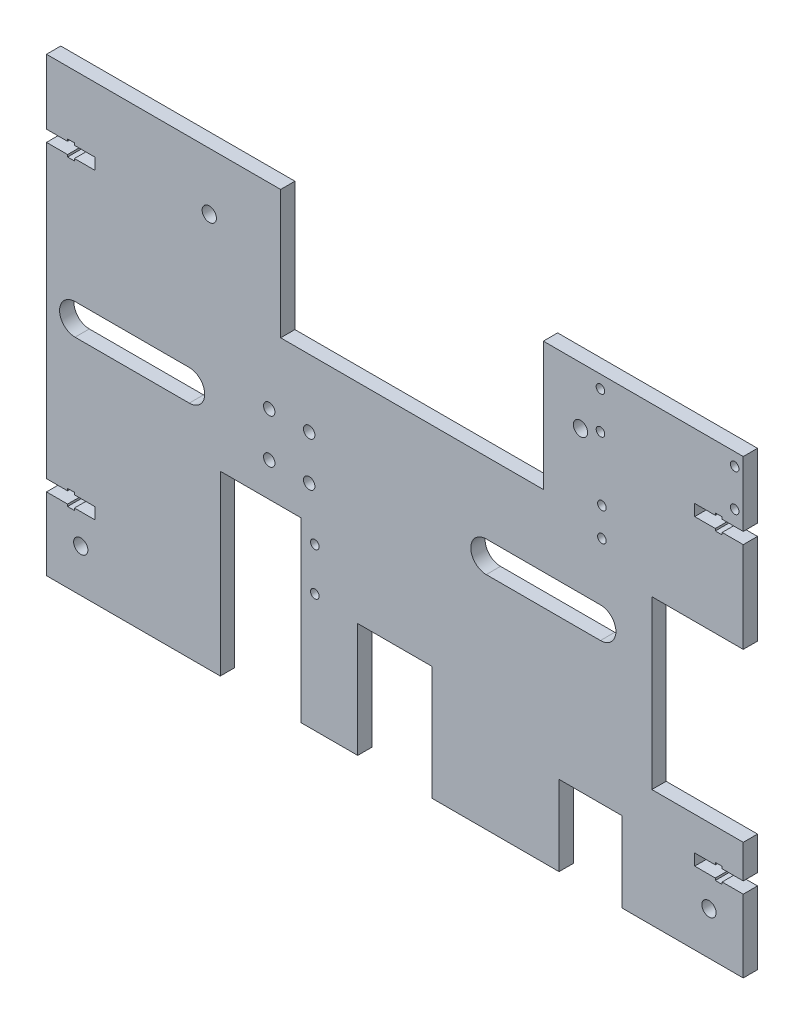
SolidWorks part; units mm, degrees
ref_plane "Front Plane" through (0, 0, 0) normal (0, 0, 1) x (1, 0, 0)
ref_plane "Top Plane" through (0, 0, 0) normal (0, 1, 0) x (1, 0, 0)
ref_plane "Right Plane" through (0, 0, 0) normal (1, 0, 0) x (0, 0, -1)
sketch "Sketch1" plane through (0, 0, 0) normal (0, 0, 1) x (1, 0, 0)
  line L8 (-125, 33.8375) -> (119, 33.8375)
  line L10 (-125, 33.8375) -> (-125, -124.317)
  line L11 (-125, -124.317) -> (119, -124.317)
  line L14 (119, -124.317) -> (119, 33.8375)
  dimension "D1" = 244
  dimension "D2" = 158.1546
extrude "Boss-Extrude2" add sketch "Sketch1" along normal blind 5
sketch "Sketch2" plane through (0, 0, 0) normal (0, 0, -1) x (-1, 0, 0)
  line L0 (125, 33.8375) -> (125, -124.317) construction
  line L1 (64.1433, -124.317) -> (35.8567, -124.317)
  line L6 (125, -124.317) -> (-119, -124.317) construction
  line L13 (35.8567, -62.1857) -> (35.8567, -124.317)
  line L14 (64.1433, -62.1857) -> (64.1433, -124.317)
  line L15 (35.8567, -62.1857) -> (64.1433, -62.1857)
  dimension "D1" = 28.2866
  dimension "D2" = 62.1313
  dimension "D3" = 60.8567
extrude "Cut-Extrude1" cut sketch "Sketch2" against normal blind 10
sketch "Sketch7" plane through (0, 0, 0) normal (0, 0, -1) x (-1, 0, 0)
  line L0 (-119, -83.1625) -> (-119, 1.3375)
  line L1 (-119, 1.3375) -> (-87, 1.3375)
  line L3 (-119, -83.1625) -> (-87, -83.1625)
  line L4 (-87, 1.3375) -> (-87, -83.1625)
  line L5 (-119, 33.8375) -> (125, 33.8375) construction
  line L9 (-119, -124.317) -> (-119, 33.8375) construction
  dimension "D1" = 32.5
  dimension "D2" = 84.5
  dimension "D3" = 32
extrude "Cut-Extrude5" cut sketch "Sketch7" against normal blind 10
sketch "Sketch9" plane through (0, 0, 0) normal (0, 0, -1) x (-1, 0, 0)
  line L0 (64.1433, -62.1857) -> (35.8567, -62.1857) construction
  line L1 (35.8567, -62.1857) -> (35.8567, -124.317) construction
  circle A0 centre (31.0266, -67.8357) radius 1.5
  circle A2 centre (31.0266, -82.8357) radius 1.5
  dimension "D1" = 3
  dimension "D2" = 3
  dimension "D3" = 5.65
  dimension "D4" = 15
  dimension "D5" = 4.8301
extrude "Cut-Extrude7" cut sketch "Sketch9" against normal blind 10
sketch "Sketch10" plane through (0, 0, 0) normal (0, 0, -1) x (-1, 0, 0)
  line L1 (125, 33.8375) -> (125, -124.317) construction
  line L3 (-10, -124.317) -> (16, -124.317)
  line L5 (35.8567, -124.317) -> (-119, -124.317) construction
  line L7 (-10, -84.317) -> (-10, -124.317)
  line L8 (16, -84.317) -> (16, -124.317)
  line L10 (16, -84.317) -> (-10, -84.317)
  dimension "D3" = 40
  dimension "D4" = 26
  dimension "D5" = 109
extrude "Cut-Extrude8" cut sketch "Sketch10" against normal blind 10
sketch "Sketch12" plane through (0, 0, 0) normal (0, 0, -1) x (-1, 0, 0)
  line L0 (-49, 33.8375) -> (-49, -11.1625)
  line L1 (-119, 33.8375) -> (125, 33.8375) construction
  line L2 (-49, -11.1625) -> (43, -11.1625)
  line L3 (43, 33.8375) -> (43, -11.1625)
  line L4 (-49, 33.8375) -> (43, 33.8375)
  line L5 (125, 33.8375) -> (125, -124.317) construction
  line L6 (-119, 1.3375) -> (-119, 33.8375) construction
  dimension "D1" = 82
  dimension "D2" = 70
  dimension "D3" = 45
extrude "Cut-Extrude10" cut sketch "Sketch12" against normal blind 10
sketch "Sketch13" plane through (0, 0, 0) normal (0, 0, -1) x (-1, 0, 0)
  line L0 (-119, 33.8375) -> (-49, 33.8375) construction
  line L1 (-49, 33.8375) -> (-49, -11.1625) construction
  line L2 (-119, -124.317) -> (-119, -83.1625) construction
  line L3 (-10, -124.317) -> (-119, -124.317) construction
  line L4 (125, 33.8375) -> (125, -124.317) construction
  circle A1 centre (-107, -109.317) radius 2.5
  circle A2 centre (113, -109.317) radius 2.5
  circle A3 centre (-62, 13.8375) radius 2.5
  circle A4 centre (68, 13.8375) radius 2.5
  dimension "D2" = 5
  dimension "D3" = 5
  dimension "D4" = 5
  dimension "D5" = 5
  dimension "D1" = 20
  dimension "D6" = 13
  dimension "D7" = 130
  dimension "D8" = 12
  dimension "D9" = 15
  dimension "D10" = 12
extrude "Cut-Extrude11" cut sketch "Sketch13" against normal blind 10
sketch "Sketch14" plane through (0, 0, 0) normal (0, 0, -1) x (-1, 0, 0)
  line L0 (-109.2131, 11.1143) -> (-102, 11.1143)
  line L1 (-111.6131, 7.1143) -> (-119, 7.1143)
  line L3 (-119, -98.8857) -> (-111.6131, -98.8857)
  line L5 (-111.6131, -98.8857) -> (-111.6131, -99.6357)
  line L7 (-111.6131, -99.6357) -> (-109.2131, -99.6357)
  line L8 (-111.6131, 11.1143) -> (-111.6131, 11.8643)
  line L9 (-119, -43.8857) -> (-47.0288, -43.8857) construction
  line L10 (-119, 33.8375) -> (-49, 33.8375) construction
  line L11 (-109.2131, -99.6357) -> (-109.2131, -98.8857)
  line L12 (-109.2131, -98.8857) -> (-102, -98.8857)
  line L13 (3, 33.8375) -> (125, 33.8375) construction
  line L14 (3, 33.8375) -> (3, -136.7517) construction
  line L15 (-119, 11.1143) -> (-111.6131, 11.1143)
  line L16 (-119, 1.3375) -> (-119, 33.8375) construction
  line L17 (-102, 11.1143) -> (-102, 7.1143)
  line L18 (-102, 7.1143) -> (-109.2131, 7.1143)
  line L19 (-111.6131, 11.8643) -> (-109.2131, 11.8643)
  line L20 (-109.2131, 11.8643) -> (-109.2131, 11.1143)
  line L21 (-109.2131, 7.1143) -> (-109.2131, 6.3643)
  line L22 (-109.2131, 6.3643) -> (-111.6131, 6.3643)
  line L23 (-111.6131, 6.3643) -> (-111.6131, 7.1143)
  line L24 (-87, 1.3375) -> (-119, 1.3375) construction
  line L25 (-119, 11.1143) -> (-119, 7.1143)
  line L26 (-102, -98.8857) -> (-102, -94.8857)
  line L27 (-102, -94.8857) -> (-109.2131, -94.8857)
  line L28 (-109.2131, -94.8857) -> (-109.2131, -94.1357)
  line L29 (-109.2131, -94.1357) -> (-111.6131, -94.1357)
  line L30 (-111.6131, -94.1357) -> (-111.6131, -94.8857)
  line L31 (-111.6131, -94.8857) -> (-119, -94.8857)
  line L32 (-119, -98.8857) -> (-119, -94.8857)
  line L33 (125, -98.8857) -> (125, -94.8857)
  line L34 (117.6131, -94.8857) -> (125, -94.8857)
  line L35 (117.6131, -94.1357) -> (117.6131, -94.8857)
  line L36 (115.2131, -94.1357) -> (117.6131, -94.1357)
  line L37 (115.2131, -94.8857) -> (115.2131, -94.1357)
  line L38 (108, -94.8857) -> (115.2131, -94.8857)
  line L39 (108, -98.8857) -> (108, -94.8857)
  line L40 (115.2131, -98.8857) -> (108, -98.8857)
  line L41 (115.2131, -99.6357) -> (115.2131, -98.8857)
  line L42 (117.6131, -99.6357) -> (115.2131, -99.6357)
  line L43 (117.6131, -98.8857) -> (117.6131, -99.6357)
  line L44 (125, -98.8857) -> (117.6131, -98.8857)
  line L45 (125, 11.1143) -> (117.6131, 11.1143)
  line L46 (117.6131, 11.1143) -> (117.6131, 11.8643)
  line L47 (117.6131, 11.8643) -> (115.2131, 11.8643)
  line L48 (115.2131, 11.8643) -> (115.2131, 11.1143)
  line L49 (115.2131, 11.1143) -> (108, 11.1143)
  line L50 (108, 11.1143) -> (108, 7.1143)
  line L51 (108, 7.1143) -> (115.2131, 7.1143)
  line L52 (115.2131, 7.1143) -> (115.2131, 6.3643)
  line L53 (115.2131, 6.3643) -> (117.6131, 6.3643)
  line L54 (117.6131, 6.3643) -> (117.6131, 7.1143)
  line L55 (117.6131, 7.1143) -> (125, 7.1143)
  line L56 (125, 11.1143) -> (125, 7.1143)
  line M9 (-119, 33.8375) -> (-119, 1.3375)
  line M13 (-119, -83.1625) -> (-119, -124.317)
  line M23 (125, -124.317) -> (125, 33.8375)
  dimension "D1" = 22.7232
  dimension "D2" = 5.7768
  dimension "D3" = 17
  dimension "D4" = 7.3869
  dimension "D5" = 2.4
  dimension "D6" = 0.75
  dimension "D7" = 0.75
  dimension "D8" = 2.4
  dimension "D9" = 77.7232
extrude "Cut-Extrude12" cut sketch "Sketch14" against normal blind 10 contours L30 L31 L3 L5 L7 L11 L12 L26 L27 L28 L29 M13 | L23 L22 L21 L18 L17 L0 L20 L19 L8 L15 L1 M9 | L54 L55 L45 L46 L47 L48 L49 L50 L51 L52 L53 M23 | L44 L34 L35 L36 L37 L38 L39 L40 L41 L42 L43 M23
sketch "Sketch15" plane through (0, 0, 0) normal (0, 0, -1) x (-1, 0, 0)
  line L0 (-119, 1.3375) -> (-119, -24.6625)
  line L1 (-119, -24.6625) -> (-87, -24.6625)
  line L2 (-87, -83.1625) -> (-87, 1.3375) construction
  line L3 (-87, -24.6625) -> (-87, 1.3375)
  line L4 (-87, 1.3375) -> (-119, 1.3375) construction
  line L5 (-119, 1.3375) -> (-87, 1.3375)
  dimension "D1" = 26
extrude "Boss-Extrude3" add sketch "Sketch15" against normal blind 5
sketch "Sketch16" plane through (0, 0, 0) normal (0, 0, -1) x (-1, 0, 0)
  line L0 (-119, -24.6625) -> (-119, 7.1143) construction
  line L1 (-119, 33.8375) -> (-49, 33.8375) construction
  circle A0 centre (-69.5, -5.7627) radius 1.5
  circle A1 centre (-69.5, -15.7627) radius 1.5
  dimension "D1" = 3
  dimension "D2" = 3
  dimension "D3" = 49.5
  dimension "D4" = 39.6002
  dimension "D5" = 10
extrude "Cut-Extrude13" cut sketch "Sketch16" against normal blind 10
sketch "Sketch17" plane through (0, 0, 0) normal (0, 0, -1) x (-1, 0, 0)
  line L0 (-119, 11.1143) -> (-119, 33.8375) construction
  line L1 (-119, 33.8375) -> (-49, 33.8375) construction
  circle A1 centre (-69, 16.3375) radius 1.5
  circle A3 centre (-69, 29.3375) radius 1.5
  circle A5 centre (-116, 16.3375) radius 1.5
  circle A7 centre (-116, 29.3375) radius 1.5
  dimension "D1" = 3
  dimension "D2" = 3
  dimension "D3" = 3
  dimension "D4" = 3
  dimension "D5" = 3
  dimension "D6" = 4.5
  dimension "D7" = 13
  dimension "D8" = 47
extrude "Cut-Extrude14" cut sketch "Sketch17" against normal blind 10
sketch "Sketch18" plane through (0, 0, 0) normal (0, 0, -1) x (-1, 0, 0)
  line L1 (-3, -11.1625) -> (-5, -11.1625)
  line L2 (-3, -11.1625) -> (-3, -84.317)
  line L3 (-3, -84.317) -> (-5, -84.317)
  line L4 (-5, -11.1625) -> (-5, -84.317)
  line L5 (16, -84.317) -> (-10, -84.317) construction
  line L7 (9, -11.1625) -> (11, -11.1625)
  line L8 (9, -11.1625) -> (9, -84.317)
  line L9 (9, -84.317) -> (11, -84.317)
  line L10 (11, -11.1625) -> (11, -84.317)
  line L11 (-119, -24.6625) -> (-119, 7.1143) construction
  dimension "D1" = 2
  dimension "D2" = 2
  dimension "D3" = 114
  dimension "D4" = 116
  dimension "D5" = 73.1546
  dimension "D6" = 12
extrude "Cut-Extrude15" [suppressed] cut sketch "Sketch18" against normal blind 1.5
sketch "Sketch19" plane through (0, 0, 0) normal (0, 0, -1) x (-1, 0, 0)
  line L0 (125, 7.1143) -> (125, -94.8857) construction
  line L2 (43, 33.8375) -> (125, 33.8375) construction
  circle A1 centre (33, -34.7303) radius 2
  circle A3 centre (47, -34.7303) radius 2
  circle A5 centre (33, -50.2303) radius 2
  circle A7 centre (47, -50.2303) radius 2
  dimension "D2" = 4
  dimension "D3" = 4
  dimension "D4" = 4
  dimension "D5" = 4
  dimension "D1" = 92
  dimension "D6" = 14
  dimension "D7" = 68.5678
  dimension "D8" = 15.5
extrude "Cut-Extrude16" cut sketch "Sketch19" against normal blind 10
sketch "Sketch20" plane through (0, 0, 0) normal (0, 0, -1) x (-1, 0, 0)
  line L1 (-76.5, -96.317) -> (-54.5, -96.317)
  line L3 (-54.5, -96.317) -> (-54.5, -124.317)
  line L5 (-76.5, -124.317) -> (-76.5, -96.317)
  line L6 (-119, -124.317) -> (-119, -98.8857) construction
  line L8 (-76.5, -124.317) -> (-54.5, -124.317)
  line L9 (-10, -124.317) -> (-119, -124.317) construction
  dimension "D1" = 42.5
  dimension "D2" = 22
  dimension "D3" = 28
extrude "Cut-Extrude17" cut sketch "Sketch20" against normal blind 10
sketch "Sketch21" plane through (0, 0, 0) normal (0, 0, -1) x (-1, 0, 0)
  line L0 (-29, -36.1625) -> (-69, -36.1625)
  line L2 (-69, -46.9681) -> (-29, -46.9681)
  line L4 (-119, 33.8375) -> (-49, 33.8375) construction
  line L5 (-119, -24.6625) -> (-119, 7.1143) construction
  line L6 (115, -36.1625) -> (75, -36.1625)
  line L7 (75, -46.9681) -> (115, -46.9681)
  line L8 (125, 7.1143) -> (125, -94.8857) construction
  line L9 (43, 33.8375) -> (125, 33.8375) construction
  arc A0 (-69, -36.1625) -> (-69, -46.9681) centre (-69, -41.5653) ccw
  arc A1 (-29, -36.1625) -> (-29, -46.9681) centre (-29, -41.5653) cw
  arc A2 (75, -36.1625) -> (75, -46.9681) centre (75, -41.5653) ccw
  arc A3 (115, -36.1625) -> (115, -46.9681) centre (115, -41.5653) cw
  dimension "D2" = 5.4028
  dimension "D6" = 5.4028
  dimension "D1" = 40
  dimension "D3" = 70
  dimension "D4" = 50
  dimension "D5" = 40
  dimension "D7" = 10
  dimension "D8" = 70
extrude "Cut-Extrude18" cut sketch "Sketch21" against normal blind 10
